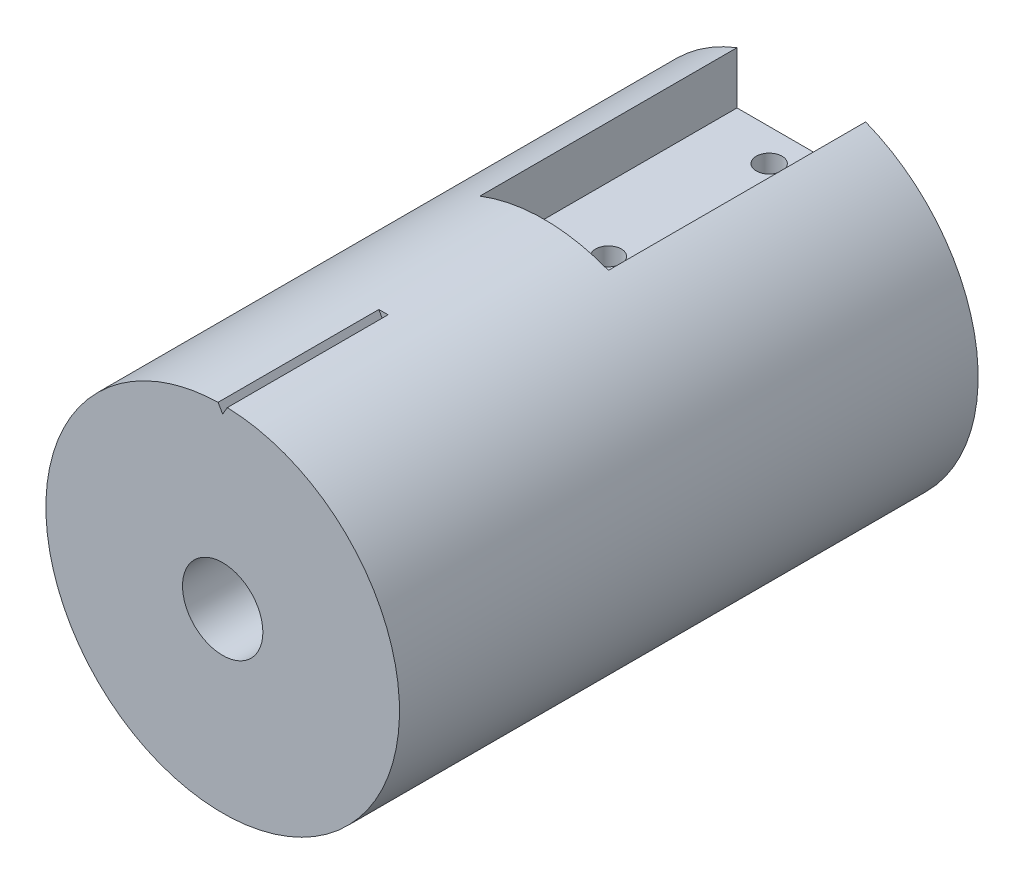
SolidWorks part; units mm, degrees
ref_plane "Front Plane" through (0, 0, 0) normal (0, 0, 1) x (1, 0, 0)
ref_plane "Top Plane" through (0, 0, 0) normal (0, 1, 0) x (1, 0, 0)
ref_plane "Right Plane" through (0, 0, 0) normal (1, 0, 0) x (0, 0, -1)
sketch "Sketch1" plane through (0, 0, 0) normal (0, 0, 1) x (1, 0, 0)
  circle A0 centre (0, 0) radius 11
  dimension "D1" = 22
extrude "Boss-Extrude1" add sketch "Sketch1" along normal blind 36
sketch "Sketch2" plane through (0, 0, 0) normal (0, 0, -1) x (-1, 0, 0)
  line L0 (0, -6.5789) -> (0, 15.632) construction
  line L10 (-4, 7) -> (4, 7)
  line L11 (-4, 7) -> (-4, 37)
  line L12 (-4, 37) -> (4, 37)
  line L13 (4, 7) -> (4, 37)
  line L14 (-4, 7) -> (4, 37) construction
  line L15 (-4, 37) -> (4, 7) construction
  point P1 (0, 22)
  dimension "D1" = 8
  dimension "D2" = 30
  dimension "D3" = 7
extrude "Cut-Extrude1" cut sketch "Sketch2" against normal blind 16
sketch "Sketch6" plane through (0, 0, 36) normal (0, 0, 1) x (1, 0, 0)
  line L0 (-0.2865, 10.9963) -> (0, 10.5)
  line L1 (0, 10.5) -> (0.2865, 10.9963)
  line L2 (0, -12.1) -> (0, 12.1) construction
  circle A0 centre (0, 0) radius 11 construction
  circle A2 centre (0, 0) radius 11
  arc A3 (0.2865, 10.9963) -> (-0.2865, 10.9963) centre (0, 0) ccw
  point P16 (0, 11)
  dimension "D1" = 60
  dimension "D2" = 0.5
  dimension "D3" = 0
extrude "Cut-Extrude3" cut sketch "Sketch6" against normal blind 10
hole_wizard "M2x0.4 Tapped Hole3" positions "Sketch14" profile "Sketch15" tap size "M2x0.4" standard "BSI" end condition up to next
sketch "Sketch14" plane through (0, 7, 0) normal (0, 1, 0) x (1, 0, 0)
  line L0 (4, -16) -> (-4, -16) construction
  point P0 (0, -12)
  point P2 (0, -2)
  dimension "D1" = 4
  dimension "D2" = 10
sketch "Sketch15" plane through (0, 7, 12) normal (1, 0, 0) x (0, 0, 1)
  line L0 (0, 0) -> (0, 18)
  line L1 (0, 18) -> (0.8, 18)
  line L2 (0.8, 18) -> (0.8, 0)
  line L5 (0.8, 0) -> (0, 0)
  line L11 (0, -6.35) -> (0, 107.95) construction
  dimension "Thru Tap Drill Dia." = 1.6
  dimension "Thru Tap Drill Depth" = 18
cosmetic thread "Hole Thread3" parameters "D2"=2
cosmetic thread "Hole Thread4" parameters "D2"=2
sketch "Sketch16" plane through (0, 0, 36) normal (0, 0, 1) x (1, 0, 0)
  circle A0 centre (0, 0) radius 2.5
  dimension "D1" = 5
extrude "Cut-Extrude4" cut sketch "Sketch16" against normal blind 8
